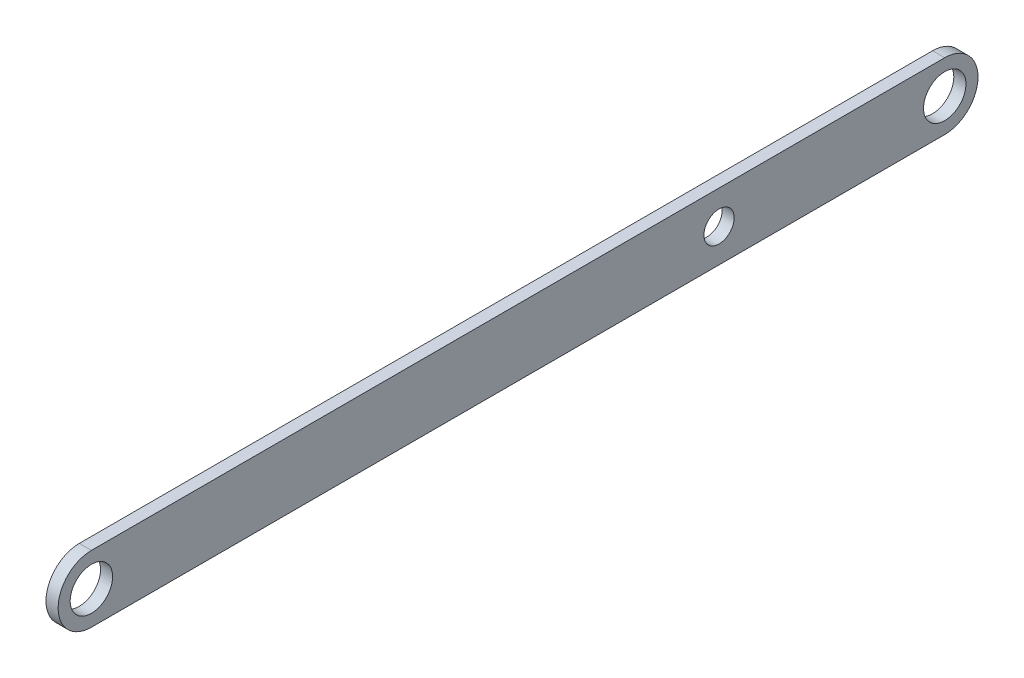
SolidWorks part; units mm, degrees
ref_plane "Front Plane" through (0, 0, 0) normal (0, 0, 1) x (1, 0, 0)
ref_plane "Top Plane" through (0, 0, 0) normal (0, 1, 0) x (1, 0, 0)
ref_plane "Right Plane" through (0, 0, 0) normal (1, 0, 0) x (0, 0, -1)
sketch "Sketch2" plane through (0, 0, 0) normal (1, 0, 0) x (0, 0, -1)
  line L0 (-77.5395, 0) -> (204.0779, 0) construction
  line L1 (-77.5395, 10.9869) -> (204.0779, 10.9869)
  line L2 (-77.5395, -10.9869) -> (204.0779, -10.9869)
  arc A0 (-77.5395, 10.9869) -> (-77.5395, -10.9869) centre (-77.5395, 0) ccw
  arc A1 (204.0779, -10.9869) -> (204.0779, 10.9869) centre (204.0779, 0) ccw
  circle A2 centre (-77.5395, 0) radius 7
  circle A3 centre (204.0779, 0) radius 7
  circle A4 centre (129.5984, 0) radius 5
  point P3 (63.2692, 0)
extrude "Boss-Extrude1" add sketch "Sketch2" along normal blind 4
